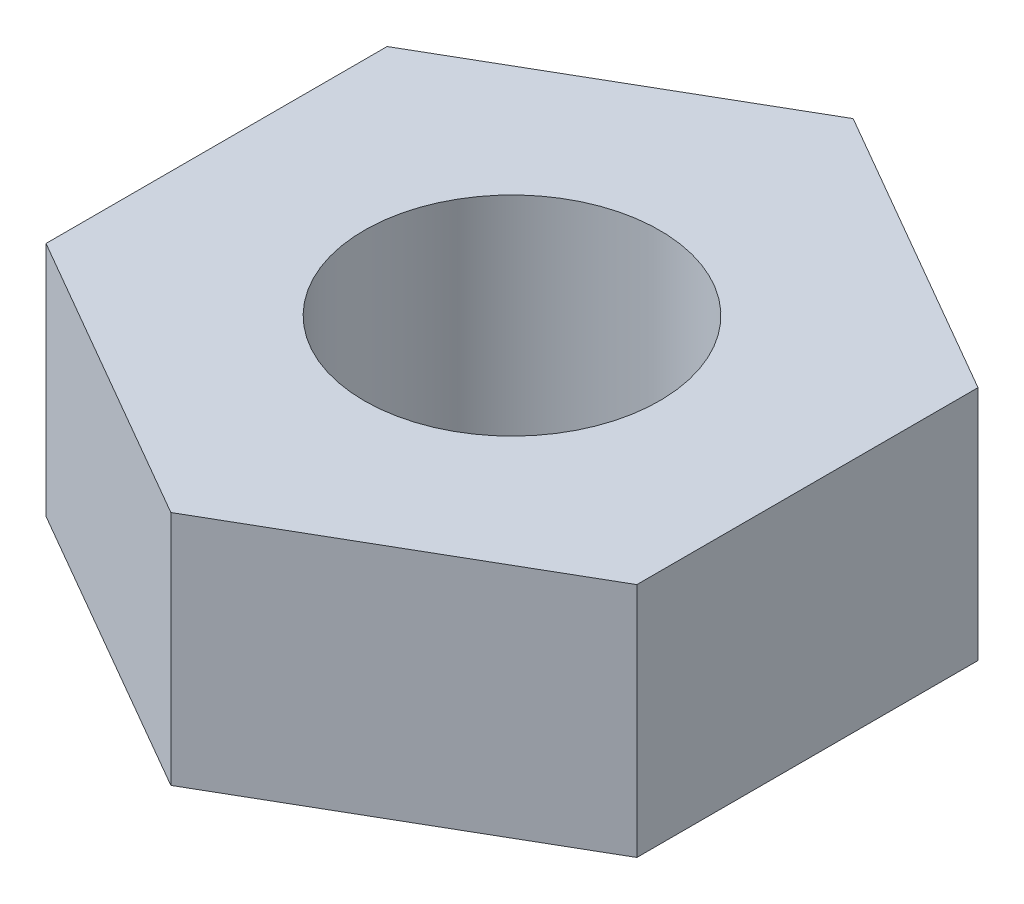
SolidWorks part; units mm, degrees
ref_plane "前视基准面" through (0, 0, 0) normal (0, 0, 1) x (1, 0, 0)
ref_plane "上视基准面" through (0, 0, 0) normal (0, 1, 0) x (1, 0, 0)
ref_plane "右视基准面" through (0, 0, 0) normal (1, 0, 0) x (0, 0, -1)
sketch "草图1" plane through (0, 0, 0) normal (0, 1, 0) x (1, 0, 0)
  line L1 (0, -2.3094) -> (2, -1.1547)
  line L2 (2, -1.1547) -> (2, 1.1547)
  line L3 (2, 1.1547) -> (0, 2.3094)
  line L4 (0, 2.3094) -> (-2, 1.1547)
  line L5 (-2, 1.1547) -> (-2, -1.1547)
  line L6 (-2, -1.1547) -> (0, -2.3094)
  circle A0 centre (0, 0) radius 2 construction
  circle A1 centre (0, 0) radius 1
  dimension "D1" = 4
extrude "凸台-拉伸1" add sketch "草图1" along normal blind 1.6
